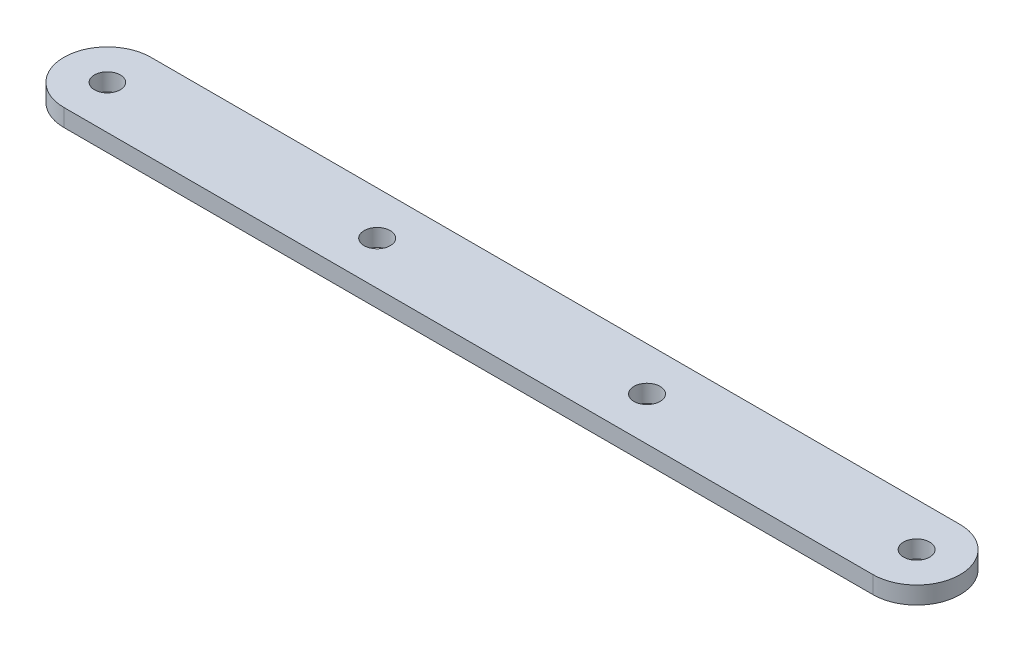
SolidWorks part; units mm, degrees
ref_plane "Front Plane" through (0, 0, 0) normal (0, 0, 1) x (1, 0, 0)
ref_plane "Top Plane" through (0, 0, 0) normal (0, 1, 0) x (1, 0, 0)
ref_plane "Right Plane" through (0, 0, 0) normal (1, 0, 0) x (0, 0, -1)
sketch "Sketch1" plane through (0, 0, 0) normal (0, 1, 0) x (1, 0, 0)
  line L0 (-124.1, 0) -> (62, 0) construction
  line L1 (-124.1, 0) -> (62, 0) construction
  line L2 (-124.1, 10) -> (62, 10)
  line L3 (-124.1, -10) -> (62, -10)
  arc A0 (-124.1, 10) -> (-124.1, -10) centre (-124.1, 0) ccw
  arc A1 (62, -10) -> (62, 10) centre (62, 0) ccw
  circle A3 centre (-124.1, 0) radius 2.975
  circle A4 centre (-62.05, 0) radius 3.01
  circle A5 centre (0, 0) radius 3.01
  circle A6 centre (62, 0) radius 3.01
  point P3 (-124.1, 0)
  point P4 (-62.05, 0)
  point P5 (62, 0)
  point P6 (-31.05, 0)
  point P11 (-186.4, 0)
  point P12 (-145.8095, 0)
  point P21 (58.99, 0)
  point P22 (0, 0)
  point P23 (0, 0)
  point P24 (-124.1, 0)
  point P25 (0, 0)
  point P26 (0, 0)
  point P27 (62, 0)
  dimension "D6" = 20
  dimension "D1" = 5.95
  dimension "D2" = 62.05
  dimension "D3" = 62.05
  dimension "D4" = 62
extrude "Boss-Extrude1" add sketch "Sketch1" along normal blind 4
